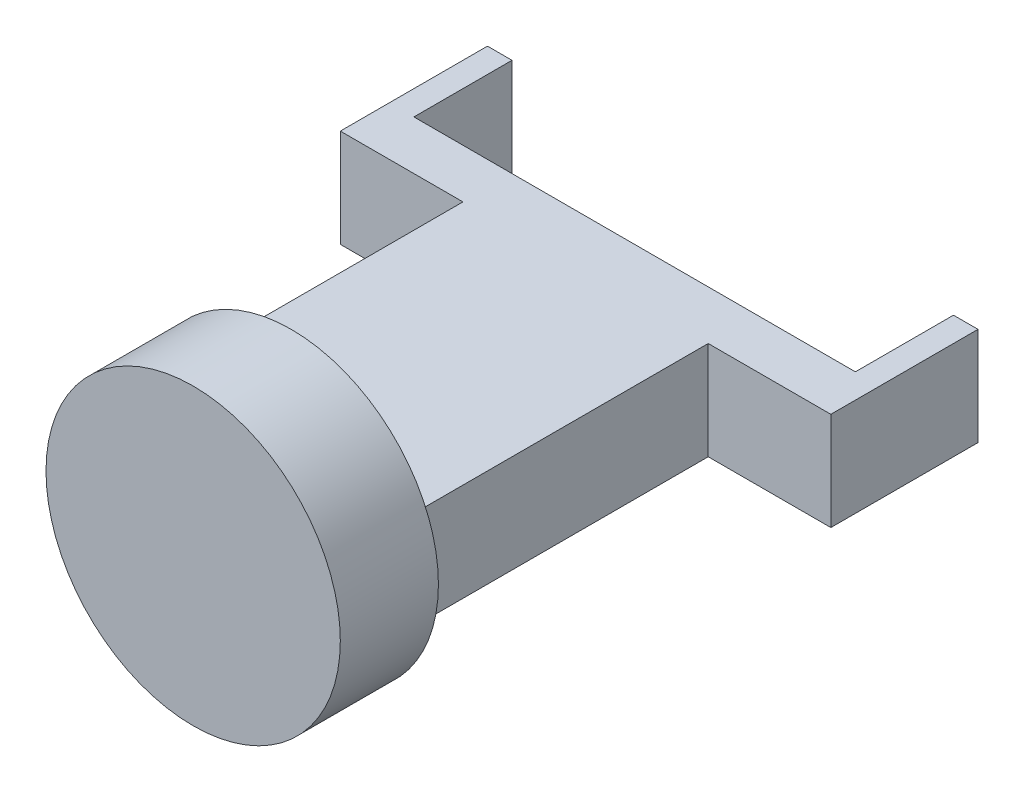
SolidWorks part; units mm, degrees
ref_plane "Front Plane" through (0, 0, 0) normal (0, 0, 1) x (1, 0, 0)
ref_plane "Top Plane" through (0, 0, 0) normal (0, 1, 0) x (1, 0, 0)
ref_plane "Right Plane" through (0, 0, 0) normal (1, 0, 0) x (0, 0, -1)
sketch "Sketch1" plane through (0, 0, 0) normal (0, 0, 1) x (1, 0, 0)
  circle A1 centre (0, 0) radius 30
  dimension "D1" = 60
sketch "Sketch2" plane through (0, 0, 0) normal (0, 0, 1) x (1, 0, 0)
extrude "Boss-Extrude1" add sketch "Sketch1" against normal blind 20
sketch "Sketch3" plane through (0, 0, -20) normal (0, 0, -1) x (-1, 0, 0)
  line L1 (-25, -10) -> (25, -10)
  line L2 (-25, -10) -> (-25, 10)
  line L3 (-25, 10) -> (25, 10)
  line L4 (25, -10) -> (25, 10)
  line L5 (-25, -10) -> (25, 10) construction
  line L6 (-25, 10) -> (25, -10) construction
  point P0 (0, 0)
  dimension "D1" = 50
  dimension "D2" = 20
extrude "Boss-Extrude2" add sketch "Sketch3" along normal blind 60
sketch "Sketch4" plane through (0, 0, -80) normal (0, 0, -1) x (-1, 0, 0)
  line L1 (-50, -10) -> (50, -10)
  line L2 (-50, -10) -> (-50, 10)
  line L3 (-50, 10) -> (50, 10)
  line L4 (50, -10) -> (50, 10)
  line L5 (-50, -10) -> (50, 10) construction
  line L6 (-50, 10) -> (50, -10) construction
  point P0 (0, 0)
  dimension "D1" = 20
  dimension "D2" = 100
extrude "Boss-Extrude3" add sketch "Sketch4" along normal blind 10
sketch "Sketch5" plane through (0, 0, -90) normal (0, 0, -1) x (-1, 0, 0)
  line L0 (-50, -10) -> (-45, -10)
  line L1 (-50, -10) -> (50, -10) construction
  line L2 (-45, -10) -> (-45, 10)
  line L3 (50, 10) -> (-50, 10) construction
  line L4 (-45, 10) -> (-50, 10)
  line L5 (-50, 10) -> (-50, -10)
  line L6 (50, -10) -> (45, -10)
  line L7 (45, -10) -> (45, 10)
  line L8 (45, 10) -> (50, 10)
  line L9 (50, 10) -> (50, -10)
  dimension "D1" = 5
  dimension "D2" = 5
extrude "Boss-Extrude4" add sketch "Sketch5" along normal blind 20
